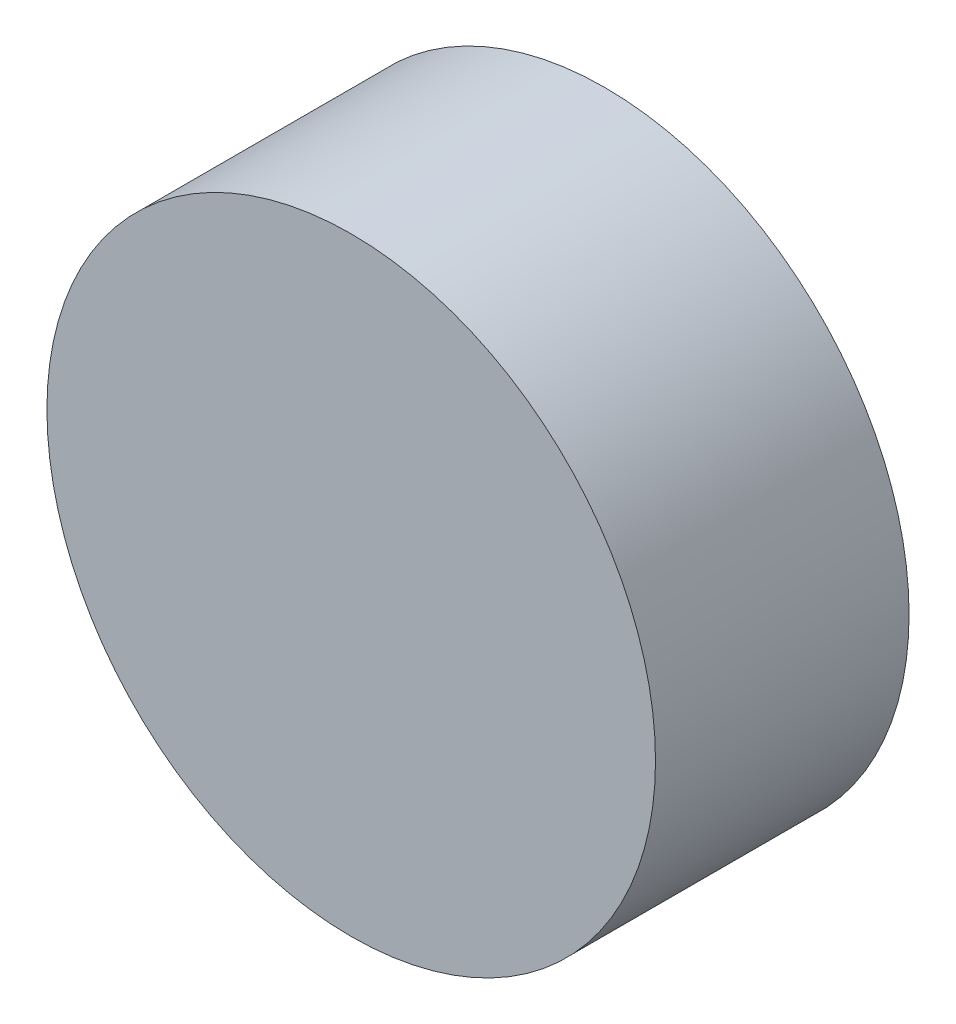
SolidWorks part; units mm, degrees
ref_plane "前基準面" through (0, 0, 0) normal (0, 0, 1) x (1, 0, 0)
ref_plane "上基準面" through (0, 0, 0) normal (0, 1, 0) x (1, 0, 0)
ref_plane "右基準面" through (0, 0, 0) normal (1, 0, 0) x (0, 0, -1)
sketch "草圖1" plane through (0, 0, 0) normal (0, 0, 1) x (1, 0, 0)
  circle A0 centre (6.3003, 8.2999) radius 3.6
extrude "填料-伸長1" add sketch "草圖1" against normal blind 3
